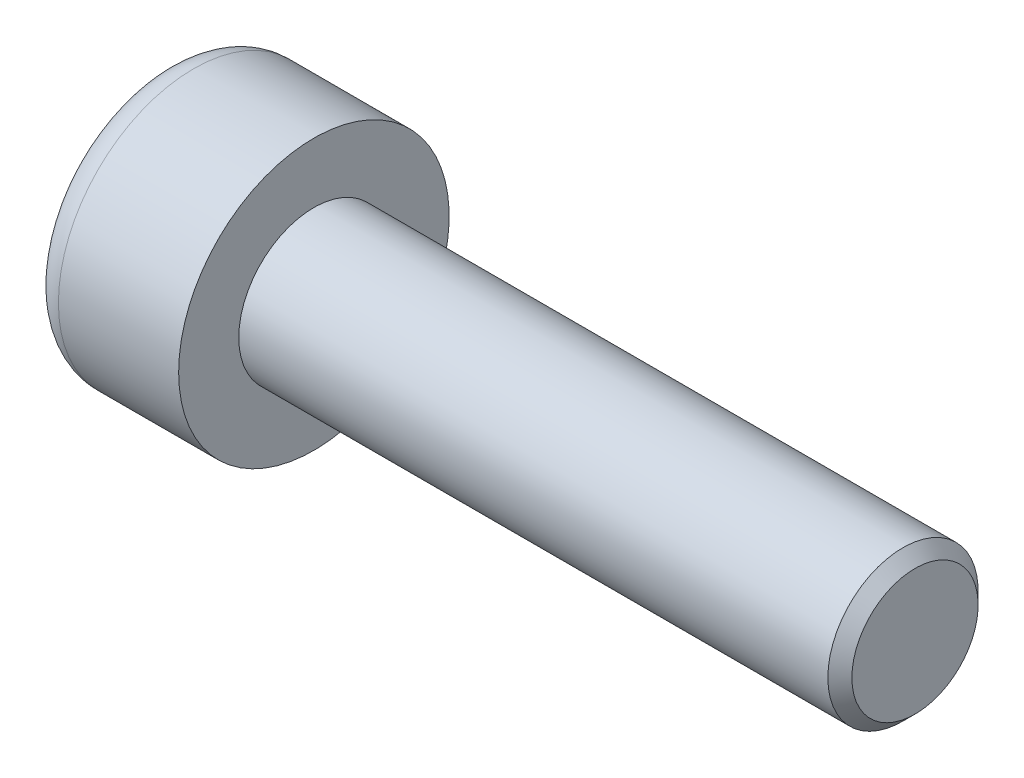
SolidWorks part; units mm, degrees
ref_plane "Face" through (0, 0, 0) normal (0, 0, 1) x (1, 0, 0)
ref_plane "Dessus" through (0, 0, 0) normal (0, 1, 0) x (1, 0, 0)
ref_plane "Droite" through (0, 0, 0) normal (1, 0, 0) x (0, 0, -1)
sketch "Esquisse1" plane through (0, 0, 0) normal (0, 0, 1) x (1, 0, 0)
  line L0 (-28.9827, 0) -> (28.9827, 0) construction
  line L1 (-2.5, 0) -> (-2.5, 2.25)
  line L2 (-2.5, 2.25) -> (0, 2.25)
  line L3 (0, 2.25) -> (0, 1.25)
  line L4 (0, 1.25) -> (10, 1.25)
  line L5 (10, 1.25) -> (10, 0)
  line L6 (10, 0) -> (-2.5, 0)
  dimension "D1" = 1.25
  dimension "D2" = 10
  dimension "D3" = 2.25
  dimension "D4" = 2.5
revolve "Base-Révolution" add sketch "Esquisse1" angle 360 about L0
chamfer "Chanfrein1" distance 0.2 angle 45 1 edges at (10, 0, 1.25)
fillet "Congé1" radius 0.5 1 edges at (-2.5, 0, 2.25)
sketch "Esquisse2" plane through (-2.5, 0, 0) normal (-1, 0, 0) x (0, 0, 1)
  line L0 (0.5774, -1) -> (-0.5774, -1)
  line L1 (-0.5774, -1) -> (-1.1547, 0)
  line L2 (-1.1547, 0) -> (-0.5774, 1)
  line L3 (-0.5774, 1) -> (0.5774, 1)
  line L4 (0.5774, 1) -> (1.1547, 0)
  line L5 (1.1547, 0) -> (0.5774, -1)
  circle A0 centre (0, 0) radius 1 construction
  dimension "D1" = 2
  dimension "D2" = 120
  dimension "D3" = 120
  dimension "D4" = 120
  dimension "D5" = 120
extrude "Empreinte pour clé" cut sketch "Esquisse2" against normal blind 2.5
